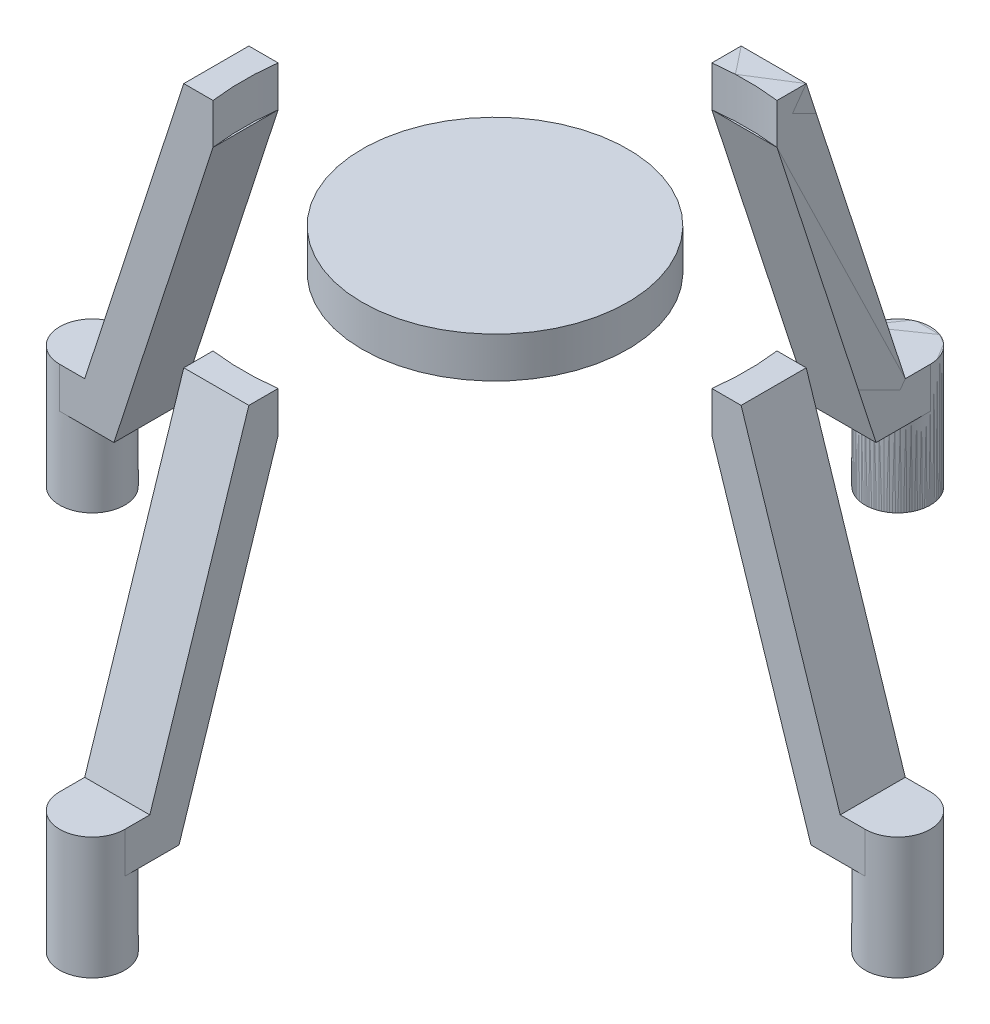
SolidWorks part; units mm, degrees
ref_plane "Front Plane" through (0, 0, 0) normal (0, 0, 1) x (1, 0, 0)
ref_plane "Top Plane" through (0, 0, 0) normal (0, 1, 0) x (1, 0, 0)
ref_plane "Right Plane" through (0, 0, 0) normal (1, 0, 0) x (0, 0, -1)
sketch "Sketch1" plane through (0, 0, 0) normal (0, 1, 0) x (1, 0, 0)
  circle A0 centre (0, 0) radius 12.55
  circle A1 centre (0, 0) radius 18.55
  dimension "D1" = 25.1
  dimension "D2" = 6
extrude "Boss-Extrude1" add sketch "Sketch1" along normal blind 3
ref_plane "Plane1" through (0, -22.5, 0) normal (0, -1, 0) x (-1, 0, 0)
sketch "Sketch3" plane through (0, -22.5, 0) normal (0, -1, 0) x (-1, 0, 0)
  circle A0 centre (0, 29.7) radius 2.4
  dimension "D1" = 4.8
  dimension "D2" = 29.7
ref_plane "Plane2" through (0, 0, -12.55) normal (0, 0, 1) x (1, 0, 0)
sketch "Sketch4" plane through (0, 0, 0) normal (0, 0, 1) x (1, 0, 0)
  line L0 (-18.55, 0) -> (18.55, 0) construction
  line L1 (-2.4, 0) -> (2.4, 0)
  line L2 (-2.4, 0) -> (-2.4, 3)
  line L3 (-2.4, 3) -> (2.4, 3)
  line L4 (2.4, 0) -> (2.4, 3)
  line L5 (18.55, 3) -> (-18.55, 3) construction
  point P8 (0, 0)
  dimension "D1" = 4.8
extrude "Boss-Extrude4" add sketch "Sketch4" against normal blind 20.55 contours L3 L4 L1 L2
sketch "Sketch7" plane through (0, -22.5, 0) normal (0, -1, 0) x (-1, 0, 0)
  line L0 (-2.4, 29.7) -> (-2.4, 25.7)
  line L1 (-2.4, 25.7) -> (2.4, 25.7)
  line L2 (2.4, 25.7) -> (2.4, 29.7)
  circle A0 centre (0, 29.7) radius 2.4 construction
  arc A1 (2.4, 29.7) -> (-2.4, 29.7) centre (0, 29.7) ccw
  point P2 (0, 0)
  dimension "D1" = 4
sketch "Sketch8" plane through (2.4, 0, 0) normal (1, 0, 0) x (0, 0, -1)
  line L0 (18.3941, 0) -> (25.7, -22.5)
  line L1 (25.7, -22.5) -> (29.7, -22.5) construction
  line L2 (20.55, 3) -> (28.83, -22.5)
  line L5 (28.83, -22.5) -> (25.7, -22.5)
  line L6 (20.55, 3) -> (18.3941, 3) construction
  line L7 (20.55, 3) -> (18.3941, 0)
  line L8 (29.7, -22.5) -> (25.7, -22.5) construction
  point P4 (25.7, -22.5)
  point P8 (27.9901, -19.5)
  point P15 (29.3531, -22.5)
  point P17 (0, 0)
  point P18 (0, 0)
extrude "Boss-Extrude6" add sketch "Sketch8" against normal up to surface (4.8 mm away) contours L0 L7 L2 L5 up to face at (-2.4, 1.5, -19.472)
extrude "Boss-Extrude7" add sketch "Sketch3" along normal blind 6 contours A0
extrude "Boss-Extrude8" add sketch "Sketch7" against normal blind 3
pattern_circular "CirPattern6" count 2 over 360 about axis through (0, 0, 0) along (0, 1, 0) of "Boss-Extrude4", "Boss-Extrude6", "Boss-Extrude7", "Boss-Extrude8"
sketch "Sketch10" plane through (0, 3, 0) normal (0, 1, 0) x (1, 0, 0)
  circle A0 centre (0, 0) radius 18.55
extrude "Cut-Extrude1" cut sketch "Sketch10" against normal blind 3
sketch "Sketch11" plane through (0, 0, 0) normal (0, 1, 0) x (1, 0, 0)
  circle A0 centre (0, 0) radius 9.7962
extrude "Boss-Extrude9" add sketch "Sketch11" along normal blind 3 separate body
pattern_circular "CirPattern7" count 4 over 360 about axis through (0, 0, 0) along (0, 1, 0) of bodies 114
equation "\"Peg Diameter\"= 4.8"
equation "\"D1@Sketch3\"=\"Peg Diameter\""
equation "\"Ring Thickness\"=6"
equation "\"D2@Sketch1\"=\"Ring Thickness\""
equation "\"D1@Sketch4\"=\"Peg Diameter\""
equation "\"Ring Height\"= 3"
equation "\"D1@Boss-Extrude1\"=\"Ring Height\""
equation "\"D1@Boss-Extrude8\"=\"Ring Height\""
